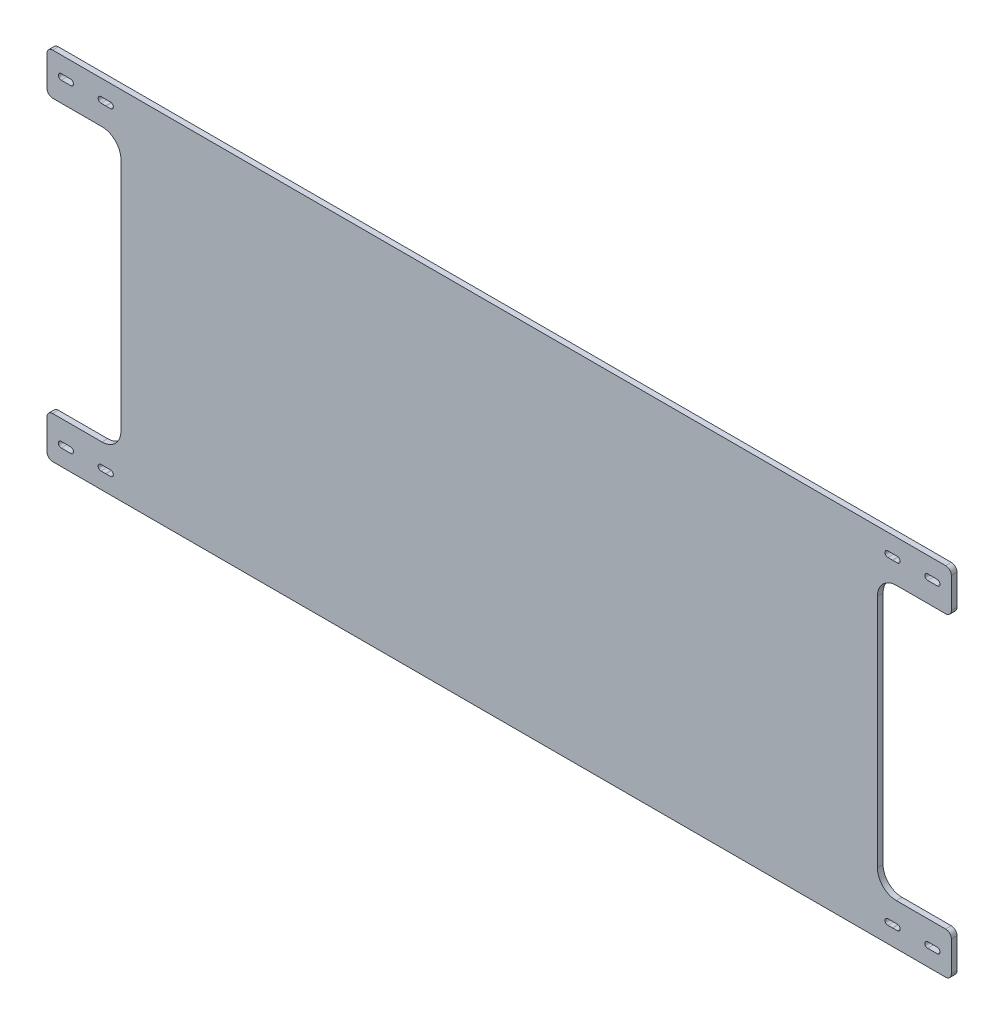
SolidWorks part; units mm, degrees
ref_plane "前视基准面" through (0, 0, 0) normal (0, 0, 1) x (1, 0, 0)
ref_plane "上视基准面" through (0, 0, 0) normal (0, 1, 0) x (1, 0, 0)
ref_plane "右视基准面" through (0, 0, 0) normal (1, 0, 0) x (0, 0, -1)
sketch "草图1" plane through (0, 0, 0) normal (0, 0, 1) x (1, 0, 0)
  line L1 (-238.5, 94) -> (238.5, 94)
  line L2 (-238.5, 94) -> (-238.5, -94)
  line L3 (-238.5, -94) -> (238.5, -94)
  line L4 (238.5, 94) -> (238.5, -94)
  line L5 (-238.5, 94) -> (238.5, -94) construction
  line L6 (-238.5, -94) -> (238.5, 94) construction
  point P0 (0, 0)
  dimension "D1" = 477
  dimension "D2" = 188
extrude "凸台-拉伸1" add sketch "草图1" along normal blind 3
sketch "草图2" plane through (0, 0, 3) normal (0, 0, 1) x (1, 0, 0)
  line L0 (0, 0) -> (0, 94) construction
  line L1 (238.5, 94) -> (-238.5, 94) construction
  line L2 (0, 0) -> (238.5, 0) construction
  line L3 (238.5, -94) -> (238.5, 94) construction
  line L4 (228.5, -84) -> (207.5, -84) construction
  circle A0 centre (228.5, 84) radius 1.5
  circle A1 centre (-228.5, 84) radius 1.5
  circle A2 centre (-228.5, -84) radius 1.5
  circle A3 centre (228.5, -84) radius 1.5
  circle A4 centre (207.5, -84) radius 1.5023
  circle A5 centre (207.5, 84) radius 1.5023
  circle A6 centre (-207.5, -84) radius 1.5023
  circle A7 centre (-207.5, 84) radius 1.5023
  dimension "D1" = 457
  dimension "D2" = 168
  dimension "D3" = 3
  dimension "D4" = 3.0047
  dimension "D5" = 21
extrude "切除-拉伸1" cut sketch "草图2" against normal through all
sketch "草图3" plane through (0, 0, 3) normal (0, 0, 1) x (1, 0, 0)
  line L0 (238.5, -72) -> (199.5, -72)
  line L1 (238.5, -94) -> (238.5, 94) construction
  line L2 (199.5, -72) -> (199.5, 72)
  line L4 (199.5, 72) -> (238.5, 72)
  line L6 (238.5, 72) -> (238.5, -72)
  line L7 (0, 0) -> (0, 94) construction
  line L8 (238.5, 94) -> (-238.5, 94) construction
  line L9 (-199.5, 72) -> (-238.5, 72)
  line L10 (-199.5, -72) -> (-199.5, 72)
  line L11 (-238.5, -72) -> (-199.5, -72)
  line L12 (-238.5, 72) -> (-238.5, -72)
  circle A0 centre (228.5, -84) radius 1.5 construction
  circle A1 centre (228.5, 84) radius 1.5 construction
  dimension "D1" = 12
  dimension "D2" = 12
  dimension "D3" = 39
sketch "草图4" plane through (0, 0, 3) normal (0, 0, 1) x (1, 0, 0)
  line L0 (-231, 84) -> (-226, 84) construction
  line L1 (-231, 85.5) -> (-226, 85.5)
  line L2 (-231, 82.5) -> (-226, 82.5)
  line L3 (-210, 84) -> (-205, 84) construction
  line L4 (-210, 85.5) -> (-205, 85.5)
  line L5 (-210, 82.5) -> (-205, 82.5)
  line L6 (0, 94) -> (0, 0) construction
  line L7 (238.5, 94) -> (-238.5, 94) construction
  line L8 (231, 84) -> (226, 84) construction
  line L9 (231, 85.5) -> (226, 85.5)
  line L10 (231, 82.5) -> (226, 82.5)
  line L11 (210, 84) -> (205, 84) construction
  line L12 (210, 85.5) -> (205, 85.5)
  line L13 (210, 82.5) -> (205, 82.5)
  arc A0 (-231, 85.5) -> (-231, 82.5) centre (-231, 84) ccw
  arc A1 (-226, 82.5) -> (-226, 85.5) centre (-226, 84) ccw
  arc A2 (-210, 85.5) -> (-210, 82.5) centre (-210, 84) ccw
  arc A3 (-205, 82.5) -> (-205, 85.5) centre (-205, 84) ccw
  circle A4 centre (-207.5, 84) radius 1.5023 construction
  arc A5 (231, 85.5) -> (231, 82.5) centre (231, 84) cw
  arc A6 (226, 82.5) -> (226, 85.5) centre (226, 84) cw
  arc A7 (210, 85.5) -> (210, 82.5) centre (210, 84) cw
  arc A8 (205, 82.5) -> (205, 85.5) centre (205, 84) cw
  point P2 (-228.5, 84)
  point P11 (-207.5, 84)
  point P24 (228.5, 84)
  point P31 (207.5, 84)
  dimension "D1" = 1.5
  dimension "D4" = 1.5
  dimension "D2" = 5
  dimension "D3" = 5
extrude "切除-拉伸3" cut sketch "草图4" against normal blind 10
mirror "镜向1" about plane through (0, 0, 0) normal (0, 1, 0) of "切除-拉伸3"
extrude "切除-拉伸4" cut sketch "草图3" against normal blind 10
fillet "圆角1" radius 10 4 edges at (199.5, -72, 1.5) (199.5, 72, 1.5) (-199.5, -72, 1.5) (-199.5, 72, 1.5)
fillet "圆角2" radius 3 8 edges at (238.5, 72, 1.5) (238.5, 94, 1.5) (238.5, -72, 1.5) (238.5, -94, 1.5) (-238.5, 72, 1.5) (-238.5, 94, 1.5) (-238.5, -72, 1.5) (-238.5, -94, 1.5)
sketch "草图5" plane through (0, 0, 0) normal (1, 0, 0) x (0, 0, -1)
  line L0 (0, 0) -> (-107.6776, 0)
